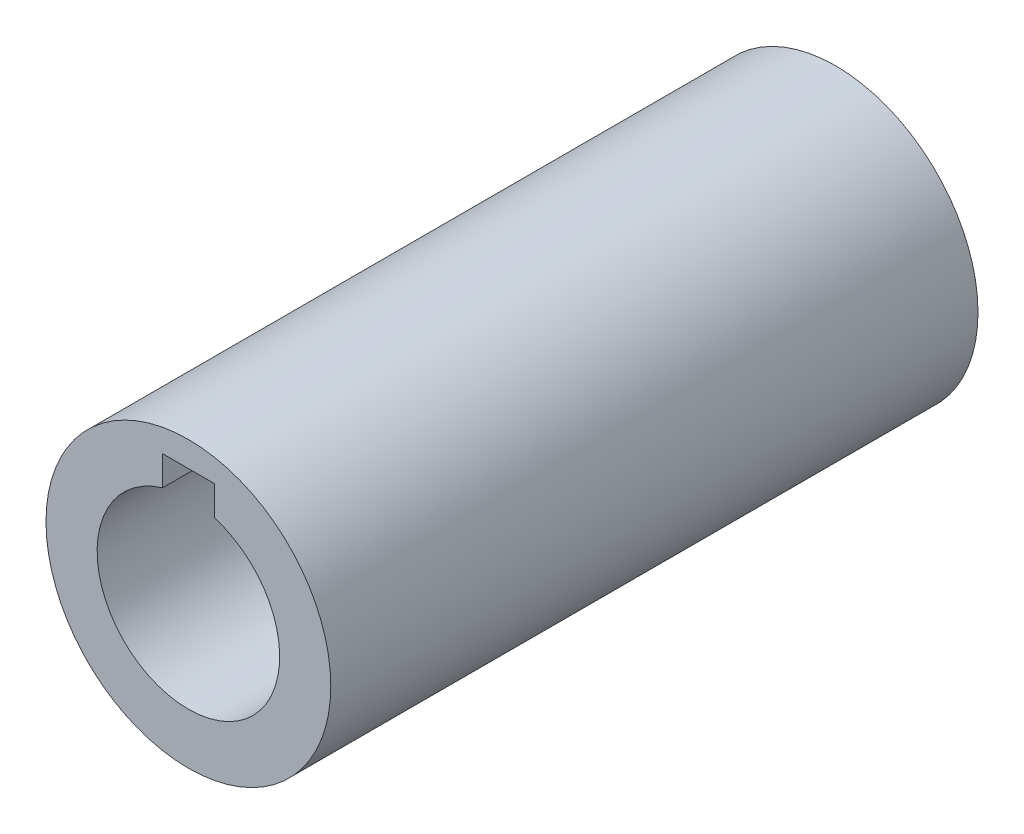
SolidWorks part; units mm, degrees
ref_plane "Front Plane" through (0, 0, 0) normal (0, 0, 1) x (1, 0, 0)
ref_plane "Top Plane" through (0, 0, 0) normal (0, 1, 0) x (1, 0, 0)
ref_plane "Right Plane" through (0, 0, 0) normal (1, 0, 0) x (0, 0, -1)
sketch "Sketch1" plane through (0, 0, 0) normal (0, 0, 1) x (1, 0, 0)
  circle A0 centre (0, 0) radius 14.1
  circle A1 centre (0, 0) radius 22
extrude "Boss-Extrude1" add sketch "Sketch1" along normal blind 100
sketch "Sketch2" plane through (0, 0, 0) normal (0, 0, -1) x (-1, 0, 0)
  line L1 (0, 18.1) -> (4, 18.1)
  line L2 (0, 18.1) -> (-4, 18.1)
  line L3 (-4, 18.1) -> (-4, 12.1)
  line L5 (4, 12.1) -> (4, 18.1)
  line L6 (-4, 12.1) -> (4, 12.1)
extrude "Cut-Extrude1" cut sketch "Sketch2" against normal through all contours L2 L3 L6 L5 L1
